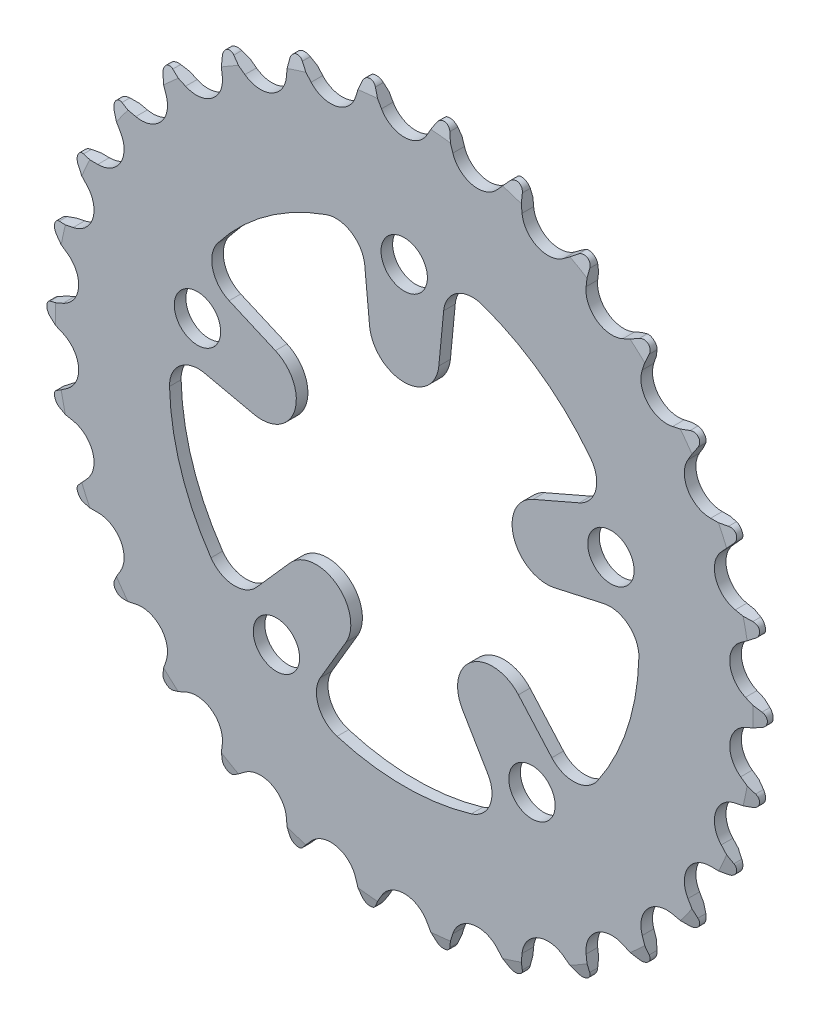
SolidWorks part; units mm, degrees
ref_plane "Alzado" through (0, 0, 0) normal (0, 0, 1) x (1, 0, 0)
ref_plane "Planta" through (0, 0, 0) normal (0, 1, 0) x (1, 0, 0)
ref_plane "Vista lateral" through (0, 0, 0) normal (1, 0, 0) x (0, 0, -1)
sketch "Croquis6" plane through (0, 0, 0) normal (1, 0, 0) x (0, 0, -1)
  line L0 (-65.0141, 61) -> (71.3388, 61) construction
  line L1 (-58.1126, 0) -> (112.1133, 0) construction
  line L2 (0, 96.3082) -> (0, -40.9059) construction
  line L3 (-1, 0) -> (-1, 61)
  line L6 (-1, 0) -> (0, 0)
  line L9 (1, 0) -> (1, 61)
  line L10 (1, 0) -> (0, 0)
  line L11 (-1, 61) -> (1, 61)
  point P9 (0, 0)
  dimension "D1" = 61
  dimension "D3" = 1
revolve "Revolución2" add sketch "Croquis6" angle 360 about L1
sketch "Croquis7" plane through (0, 0, 0) normal (0, 0, 1) x (1, 0, 0)
  line L0 (0, 72.4213) -> (0, -43.4528) construction
  line L1 (-4.178, 57.7004) -> (-5.4218, 69.5342) construction
  line L2 (4.178, 57.7004) -> (5.4218, 69.5342) construction
  line L3 (-3.9166, 58.7841) -> (-5.3272, 61.2773)
  line L4 (3.9166, 58.7841) -> (5.3272, 61.2773)
  line L5 (0, 0) -> (-14.4701, 68.0766) construction
  arc A0 (-3.9166, 58.7841) -> (3.9166, 58.7841) centre (0, 61) ccw
  circle A1 centre (0, 0) radius 61 construction
  arc A2 (-5.3272, 61.2773) -> (-6.5466, 61.9048) centre (-6.4151, 60.6617) ccw
  arc A3 (6.5466, 61.9048) -> (-6.5466, 61.9048) centre (0, 0) ccw
  arc A4 (5.3272, 61.2773) -> (6.5466, 61.9048) centre (6.4151, 60.6617) cw
  dimension "D1" = 4.5
  dimension "D5" = 1.25
  dimension "D2" = 12
  dimension "D3" = 6
  dimension "D4" = 17.5
extrude "Cortar-Extruir1" cut sketch "Croquis7" against normal through all both and the other way through all
pattern_circular "MatrizC1" count 30 over 360 about axis through (0, 0, 0) along (0, 0, 1) of "Cortar-Extruir1"
sketch "Croquis8" plane through (0, 0, 1) normal (0, 0, 1) x (1, 0, 0)
  line L0 (-20.1107, 57.5896) -> (-20.0665, 58.0487)
  line L2 (-20.3317, 55.295) -> (-20.1107, 57.5896) construction
  line L3 (-18.85, 58.0144) -> (-19.2085, 59.1177) construction
  line L4 (-17.5804, 58.4117) -> (-17.8861, 58.7572)
  arc A0 (-17.5804, 58.4117) -> (-20.1107, 57.5896) centre (0, 0) ccw construction
  arc A1 (-20.0665, 58.0487) -> (-17.8861, 58.7572) centre (-18.8222, 57.9289) cw
  arc A2 (-17.5804, 58.4117) -> (-20.1107, 57.5896) centre (0, 0) ccw
  dimension "D1" = 1.25
extrude "Saliente-Extruir2" add sketch "Croquis8" against normal through all
pattern_circular "MatrizC2" count 30 over 360 about axis through (0, 0, 0) along (0, 0, 1) of "Saliente-Extruir2"
sketch "Croquis9" plane through (0, 0, 1) normal (0, 0, 1) x (1, 0, 0)
  line L0 (0, 19.8798) -> (0, 72.023) construction
  line L1 (0, 0) -> (-100.4973, 0) construction
  line L2 (0, 0) -> (-28.6378, 28.6378) construction
  line L8 (-5.9724, 25.3048) -> (-6.8064, 33.9666)
  line L9 (5.9724, 25.3048) -> (6.8064, 33.9666)
  line L10 (-28.6378, 28.6378) -> (0, 0)
  line L12 (28.6378, 28.6378) -> (0, 0)
  circle A1 centre (0, 0) radius 37.5 construction
  circle A2 centre (0, 0) radius 26 construction
  circle A3 centre (0, 37.5) radius 4
  arc A10 (28.6378, 28.6378) -> (13.443, 38.2039) centre (0, 0) ccw
  arc A11 (-5.9724, 25.3048) -> (5.9724, 25.3048) centre (0, 25.8798) ccw
  arc A12 (-6.8064, 33.9666) -> (-13.443, 38.2039) centre (-11.7834, 33.4873) ccw
  arc A13 (6.8064, 33.9666) -> (13.443, 38.2039) centre (11.7834, 33.4873) cw
  arc A15 (-13.443, 38.2039) -> (-28.6378, 28.6378) centre (0, 0) ccw
  dimension "D2" = 75
  dimension "D3" = 52
  dimension "D4" = 8
  dimension "D7" = 5.5
  dimension "D8" = 6
  dimension "D6" = 81
  dimension "D9" = 5
  dimension "D5" = 45
extrude "Cortar-Extruir2" cut sketch "Croquis9" against normal up to next
pattern_circular "MatrizC4" count 5 over 360 about axis through (0, 0, 0) along (0, 0, 1) of "Cortar-Extruir2"
sketch "Croquis12" plane through (0, 0, 0) normal (0, 1, 0) x (1, 0, 0)
  line L0 (-62.1601, 0) -> (69.6646, 0) construction
  line L1 (-62.1601, 1) -> (-62.1601, -1) construction
  line L2 (0, 9.8583) -> (0, -7.6925) construction
  line L4 (-62.1601, 0.5) -> (-60.1547, 1)
  line L5 (-59.8283, 1) -> (-60.829, 1) construction
  line L6 (-62.1601, -0.5) -> (-60.1547, -1)
  line L7 (-60.1547, 1) -> (-62.1601, 1)
  line L8 (-61.4085, 1) -> (-62.1601, 1) construction
  line L9 (-62.1601, 1) -> (-62.1601, 0.5)
  line L10 (-62.1601, -1) -> (-61.4085, -1) construction
  line L11 (-60.1547, -1) -> (-62.1601, -1)
  line L12 (-62.1601, -0.5) -> (-62.1601, -1)
  point P10 (-62.1601, 0)
  point P14 (0, 0)
  point P21 (-62.1601, 0)
  dimension "D1" = 1
  dimension "D2" = 28
revolve "Cortar-Revolución1" cut sketch "Croquis12" angle 360 about L2
